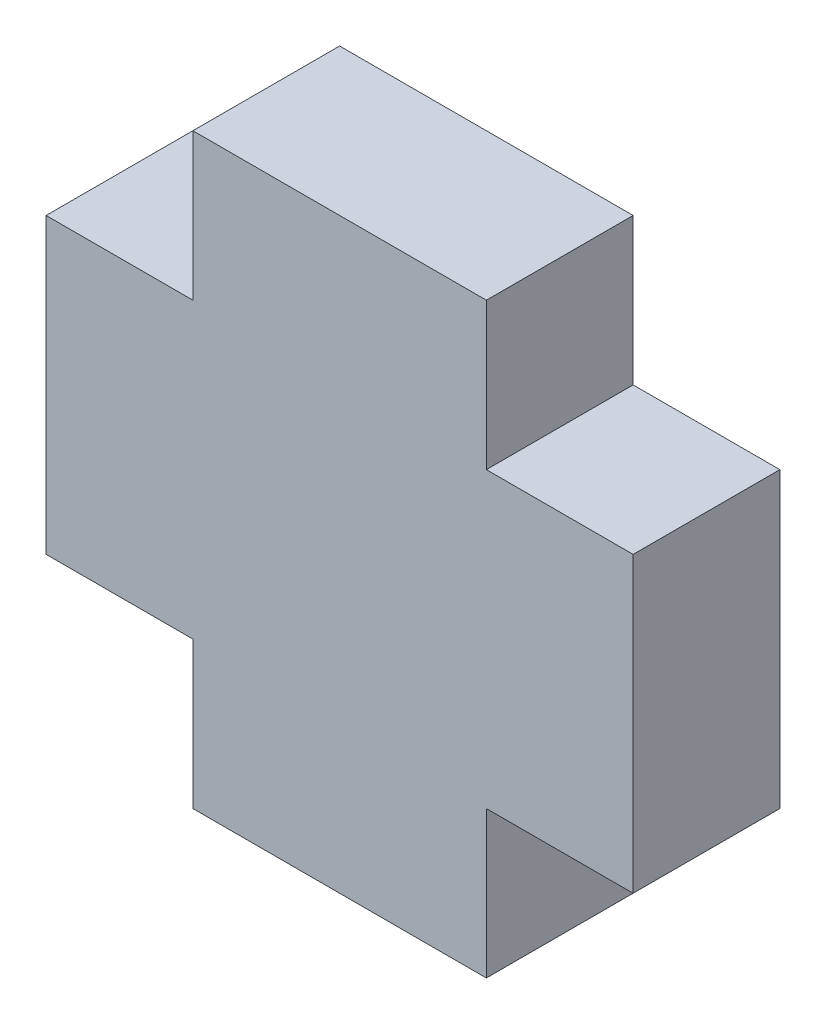
SolidWorks part; units mm, degrees
material "Beech"
ref_plane "Front" through (0, 0, 0) normal (0, 0, 1) x (1, 0, 0)
ref_plane "Top" through (0, 0, 0) normal (0, 1, 0) x (1, 0, 0)
ref_plane "Right" through (0, 0, 0) normal (1, 0, 0) x (0, 0, -1)
sketch "Sketch1" plane through (0, 0, 0) normal (0, 0, 1) x (1, 0, 0)
  line L1 (-5, -5) -> (5, -5) construction
  line L2 (-5, -5) -> (-5, 5) construction
  line L3 (-5, 5) -> (5, 5) construction
  line L4 (5, -5) -> (5, 5) construction
  line L5 (-5, -5) -> (5, 5) construction
  line L6 (-5, 5) -> (5, -5) construction
  line L10 (0, -0.7981) -> (0, 0.9877) construction
  line L11 (0.9616, 0) -> (-0.9845, 0) construction
  line L20 (-2.5, 5) -> (-2.5, 2.5)
  line L21 (-2.5, 2.5) -> (-5, 2.5)
  line L22 (-5, 2.5) -> (-5, -2.5)
  line L23 (-2.5, 5) -> (2.5, 5)
  line L24 (-2.5, -2.5) -> (-5, -2.5)
  line L25 (-2.5, -5) -> (-2.5, -2.5)
  line L26 (-2.5, -5) -> (2.5, -5)
  line L27 (2.5, -5) -> (2.5, -2.5)
  line L28 (2.5, -2.5) -> (5, -2.5)
  line L29 (5, 2.5) -> (5, -2.5)
  line L30 (2.5, 2.5) -> (5, 2.5)
  line L31 (2.5, 5) -> (2.5, 2.5)
  point P0 (0, 0)
  point P16 (-5, 0)
  point P17 (-5, 0)
  point P20 (0, -5)
  point P22 (0, -5)
  point P25 (0, 5)
  point P28 (0, 5)
  dimension "D1" = 10
  dimension "D2" = 2.5
extrude "Boss-Extrude1" add sketch "Sketch1" along normal blind 2.5
